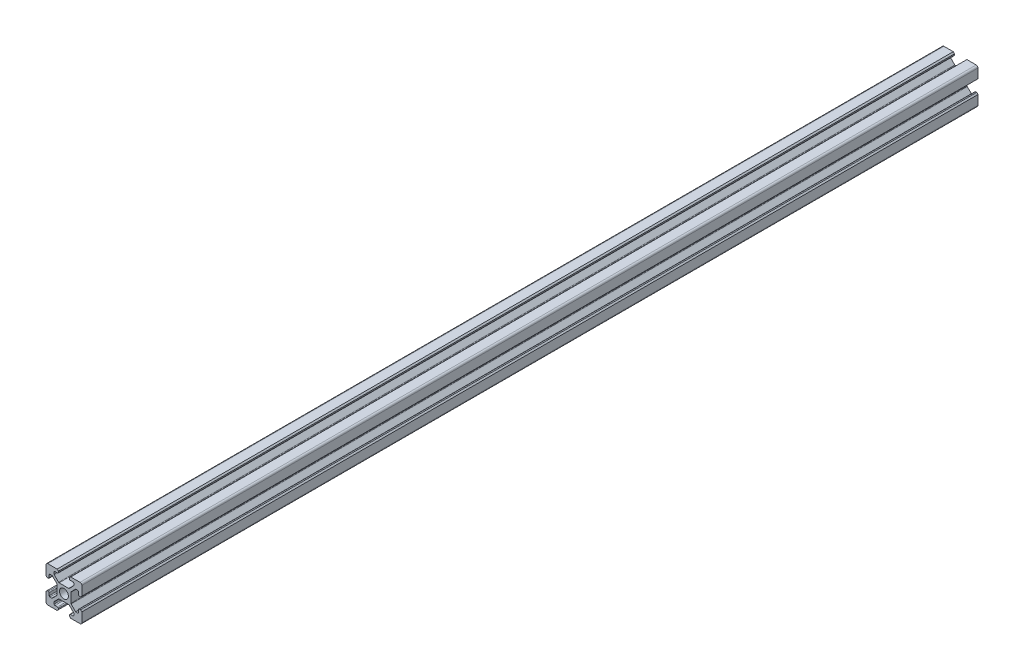
SolidWorks part; units mm, degrees
material "1060 Alloy"
ref_plane "Front Plane" through (0, 0, 0) normal (0, 0, 1) x (1, 0, 0)
ref_plane "Top Plane" through (0, 0, 0) normal (0, 1, 0) x (1, 0, 0)
ref_plane "Right Plane" through (0, 0, 0) normal (1, 0, 0) x (0, 0, -1)
sketch "Sketch1" plane through (0, 0, 0) normal (0, 0, 1) x (1, 0, 0)
  line L0 (3.9, -2.8393) -> (6.5607, -5.5)
  line L1 (-10, 10) -> (10, 10) construction
  line L2 (-10, 10) -> (-10, -10) construction
  line L3 (-10, -10) -> (10, -10) construction
  line L4 (10, 10) -> (10, -10) construction
  line L5 (-10, 10) -> (10, -10) construction
  line L6 (-10, -10) -> (10, 10) construction
  line L7 (-3.9, -3.9) -> (3.9, -3.9) construction
  line L8 (-3.9, -3.9) -> (-3.9, 3.9) construction
  line L9 (-3.9, 3.9) -> (3.9, 3.9) construction
  line L10 (3.9, -3.9) -> (3.9, 3.9) construction
  line L11 (-3.9, -3.9) -> (3.9, 3.9) construction
  line L12 (-3.9, 3.9) -> (3.9, -3.9) construction
  line L13 (-10, 10) -> (-5.5, 10) construction
  line L14 (-10, 10) -> (-10, 5.5) construction
  line L15 (-10, 5.5) -> (-5.5, 5.5) construction
  line L16 (-5.5, 10) -> (-5.5, 5.5) construction
  line L17 (10, 10) -> (5.5, 10) construction
  line L18 (10, 10) -> (10, 5.5) construction
  line L19 (10, 5.5) -> (5.5, 5.5) construction
  line L20 (5.5, 10) -> (5.5, 5.5) construction
  line L21 (-10, -10) -> (-5.5, -10) construction
  line L22 (-10, -10) -> (-10, -5.5) construction
  line L23 (-10, -5.5) -> (-5.5, -5.5) construction
  line L24 (-5.5, -10) -> (-5.5, -5.5) construction
  line L25 (10, -10) -> (5.5, -10) construction
  line L26 (10, -10) -> (10, -5.5) construction
  line L27 (10, -5.5) -> (5.5, -5.5) construction
  line L28 (5.5, -10) -> (5.5, -5.5) construction
  line L29 (2.8393, -3.9) -> (5.5, -6.5607)
  line L30 (-5.5, 6.5607) -> (-2.8393, 3.9)
  line L31 (-6.5607, 5.5) -> (-3.9, 2.8393)
  line L32 (5.5, 6.5607) -> (2.8393, 3.9)
  line L33 (6.5607, 5.5) -> (3.9, 2.8393)
  line L34 (-6.5607, -5.5) -> (-3.9, -2.8393)
  line L35 (-5.5, -6.5607) -> (-2.8393, -3.9)
  line L36 (-2.8393, 3.9) -> (2.8393, 3.9)
  line L37 (-3.9, 2.8393) -> (-3.9, -2.8393)
  line L38 (-2.8393, -3.9) -> (2.8393, -3.9)
  line L39 (3.9, -2.8393) -> (3.9, 2.8393)
  line L40 (5.5, 6.5607) -> (5.5, 8.2007)
  line L41 (5.5, 8.2007) -> (3.1, 8.2007)
  line L42 (3.1, 8.2007) -> (3.1, 9.3)
  line L43 (3.1, 9.3) -> (3.8, 10)
  line L44 (3.8, 10) -> (10, 10)
  line L45 (10, 10) -> (10, 3.8)
  line L46 (10, 3.8) -> (9.3, 3.1)
  line L47 (9.3, 3.1) -> (8.2007, 3.1)
  line L48 (8.2007, 3.1) -> (8.2007, 5.5)
  line L49 (8.2007, 5.5) -> (6.5607, 5.5)
  line L50 (3.1, -8.2007) -> (5.5, -8.2007)
  line L51 (3.1, -9.3) -> (3.1, -8.2007)
  line L52 (3.8, -10) -> (3.1, -9.3)
  line L53 (10, -10) -> (3.8, -10)
  line L54 (10, -3.8) -> (10, -10)
  line L55 (9.3, -3.1) -> (10, -3.8)
  line L56 (8.2007, -3.1) -> (9.3, -3.1)
  line L57 (8.2007, -5.5) -> (8.2007, -3.1)
  line L58 (6.5607, -5.5) -> (8.2007, -5.5)
  line L59 (5.5, -8.2007) -> (5.5, -6.5607)
  line L60 (-8.2007, -3.1) -> (-8.2007, -5.5)
  line L61 (-9.3, -3.1) -> (-8.2007, -3.1)
  line L62 (-10, -3.8) -> (-9.3, -3.1)
  line L63 (-10, -10) -> (-10, -3.8)
  line L64 (-3.8, -10) -> (-10, -10)
  line L65 (-3.1, -9.3) -> (-3.8, -10)
  line L66 (-3.1, -8.2007) -> (-3.1, -9.3)
  line L67 (-5.5, -8.2007) -> (-3.1, -8.2007)
  line L68 (-5.5, -6.5607) -> (-5.5, -8.2007)
  line L69 (-8.2007, -5.5) -> (-6.5607, -5.5)
  line L70 (-3.1, 8.2007) -> (-5.5, 8.2007)
  line L71 (-3.1, 9.3) -> (-3.1, 8.2007)
  line L72 (-3.8, 10) -> (-3.1, 9.3)
  line L73 (-10, 10) -> (-3.8, 10)
  line L74 (-10, 3.8) -> (-10, 10)
  line L75 (-9.3, 3.1) -> (-10, 3.8)
  line L76 (-8.2007, 3.1) -> (-9.3, 3.1)
  line L77 (-8.2007, 5.5) -> (-8.2007, 3.1)
  line L78 (-6.5607, 5.5) -> (-8.2007, 5.5)
  line L79 (-5.5, 8.2007) -> (-5.5, 6.5607)
  circle A0 centre (0, 0) radius 2.5
  point P83 (0, 0)
  dimension "D1" = 5
  dimension "D2" = 20
  dimension "D3" = 7.8
  dimension "D4" = 4.5
  dimension "D5" = 1.5
  dimension "D6" = 0.75
  dimension "D7" = 1.5
  dimension "D8" = 0.75
  dimension "D9" = 1.5
  dimension "D10" = 0.75
  dimension "D11" = 1.5
  dimension "D12" = 0.75
  dimension "D13" = 1.64
  dimension "D14" = 45
  dimension "D15" = 3.1
  dimension "D16" = 6.2
  dimension "D17" = 6.2
  dimension "D18" = 3.1
  dimension "D19" = 4
extrude "Boss-Extrude1" add sketch "Sketch1" along normal mid plane 500 contours L79 L70 L71 L72 L73 L74 L75 L76 L77 L78 L31 L37 L34 L69 L60 L61 L62 L63 L64 L65 L66 L67 L68 L35 L38 L29 L59 L50 L51 L52 L53 L54 L55 L56 L57 L58 L0 L39 L33 L49 L48 L47 L46 L45 L44 L43 L42 L41 L40 L32 L36
fillet "Fillet1" radius 0.5 8 edges at (2.8393, -3.9, 0) (-2.8393, -3.9, 0) (-3.9, 2.8393, 0) (-3.9, -2.8393, 0) (3.9, -2.8393, 0) (3.9, 2.8393, 0) (2.8393, 3.9, 0) (-2.8393, 3.9, 0)
fillet "Fillet2" radius 0.5 24 edges at (-8.2007, -3.1, 0) (-8.2007, -5.5, 0) (-6.5607, -5.5, 0) (-3.1, -8.2007, 0) (-5.5, -8.2007, 0) (-5.5, -6.5607, 0) (3.1, -8.2007, 0) (5.5, -6.5607, 0) (5.5, -8.2007, 0) (8.2007, -5.5, 0) (8.2007, -3.1, 0) (6.5607, -5.5, 0) (-8.2007, 3.1, 0) (-6.5607, 5.5, 0) (-8.2007, 5.5, 0) (6.5607, 5.5, 0) (8.2007, 5.5, 0) (8.2007, 3.1, 0) (5.5, 6.5607, 0) (5.5, 8.2007, 0) (3.1, 8.2007, 0) (-3.1, 8.2007, 0) (-5.5, 8.2007, 0) (-5.5, 6.5607, 0)
fillet "Fillet3" radius 1 4 edges at (-10, 10, 0) (-10, -10, 0) (10, 10, 0) (10, -10, 0)
